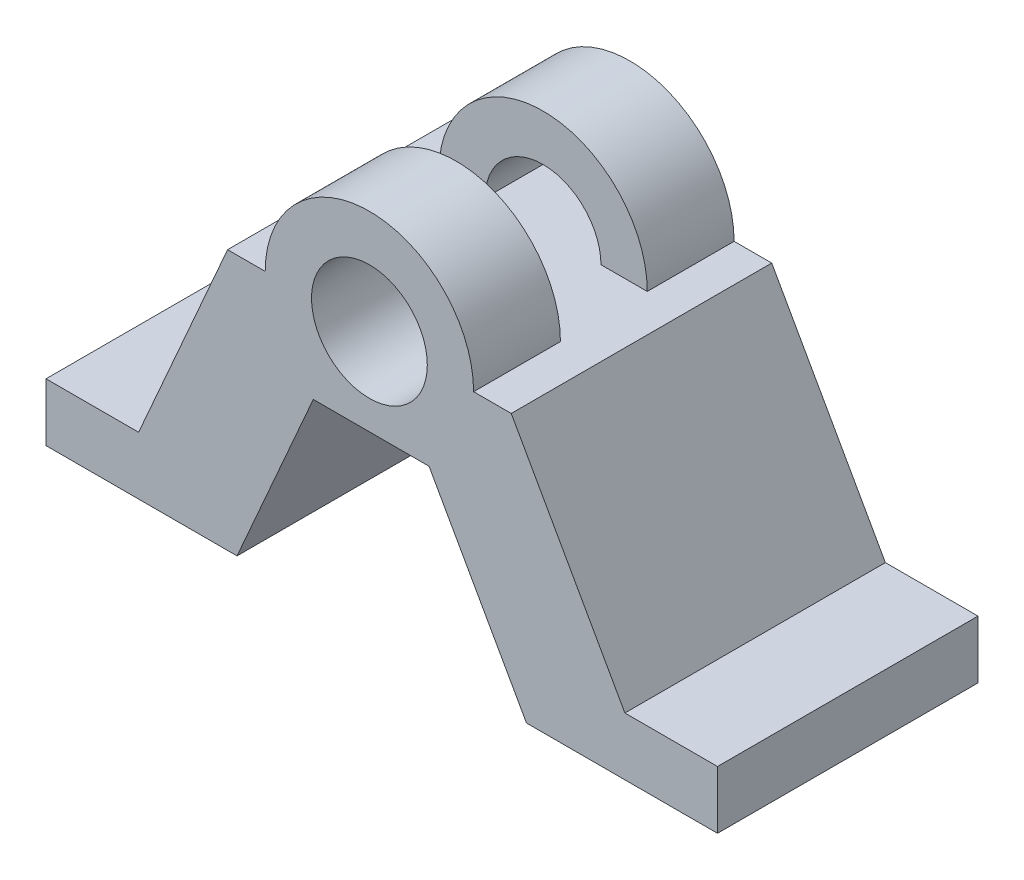
SolidWorks part; units mm, degrees
ref_plane "Front Plane" through (0, 0, 0) normal (0, 0, 1) x (1, 0, 0)
ref_plane "Top Plane" through (0, 0, 0) normal (0, 1, 0) x (1, 0, 0)
ref_plane "Right Plane" through (0, 0, 0) normal (1, 0, 0) x (0, 0, -1)
sketch "Sketch1" plane through (0, 0, 0) normal (0, 0, 1) x (1, 0, 0)
  line L0 (52.8254, 0) -> (52.8254, -10)
  line L1 (52.8254, -10) -> (19.8254, -10)
  line L2 (19.8254, -10) -> (2.998, 20)
  line L3 (2.998, 20) -> (-17.002, 20)
  line L4 (52.8254, 0) -> (36.8254, 0)
  line L5 (36.8254, 0) -> (17.1934, 35)
  line L6 (17.1934, 35) -> (5.1934, 35)
  line L7 (-17.002, 20) -> (-30.1746, -10)
  line L8 (-30.1746, -10) -> (-63.1746, -10)
  line L9 (-63.1746, -10) -> (-63.1746, 0)
  line L10 (-63.1746, 0) -> (-47.1746, 0)
  line L11 (-47.1746, 0) -> (-31.8066, 35)
  line L12 (-31.8066, 35) -> (-19.8066, 35)
  line L13 (-19.8066, 35) -> (5.1934, 35) construction
  circle A1 centre (-7.3066, 35) radius 12.5
  dimension "D13" = 40.13
  dimension "D1" = 50
  dimension "D2" = 116
  dimension "D3" = 20
  dimension "D4" = 12
  dimension "D5" = 12
  dimension "D6" = 30
  dimension "D7" = 10
  dimension "D8" = 16
  dimension "D9" = 16
  dimension "D10" = 45
  dimension "D11" = 45
  dimension "D12" = 16
  dimension "D14" = 33
  dimension "D15" = 33
extrude "Boss-Extrude2" add sketch "Sketch1" against normal blind 30 contours L13 A1 | A1 L12 L11 L10 L9 L8 L7 L3 L2 L1 L0 L4 L5 L6
sketch "Sketch4" plane through (0, 0, 0) normal (0, 0, 1) x (1, 0, 0)
  line L0 (-31.8066, 35) -> (17.1934, 35) construction
  line L1 (-25.3066, 35) -> (10.6934, 35) construction
  line L2 (-25.3066, 35) -> (10.6934, 35)
  circle A0 centre (-7.3066, 35) radius 18
  line M2 (17.1934, 35) -> (-31.8066, 35)
extrude "Boss-Extrude4" add sketch "Sketch4" against normal blind 15 contours A0 M2
ref_plane "Plane2" through (0, 0, -22.5) normal (0, 0, -1) x (-1, 0, 0)
mirror "Mirror1" about plane through (0, 0, -22.5) normal (0, 0, -1) of "Boss-Extrude2", "Boss-Extrude4"
sketch "Sketch5" plane through (0, 0, 0) normal (0, 0, 1) x (1, 0, 0)
  line L0 (-17.3066, 35) -> (2.6934, 35)
  circle A0 centre (-7.3066, 35) radius 10
extrude "Cut-Extrude1" cut sketch "Sketch5" against normal through all contours L0 A0
sketch "Sketch6" plane through (0, 0, 0) normal (0, 0, 1) x (1, 0, 0)
  line L0 (-17.3066, 35) -> (2.6934, 35) construction
  line L1 (-17.3066, 35) -> (2.6934, 35)
  circle A0 centre (-7.3066, 35) radius 10
  line M2 (2.6934, 35) -> (-17.3066, 35)
extrude "Cut-Extrude2" cut sketch "Sketch6" against normal blind 15 contours A0 M2
